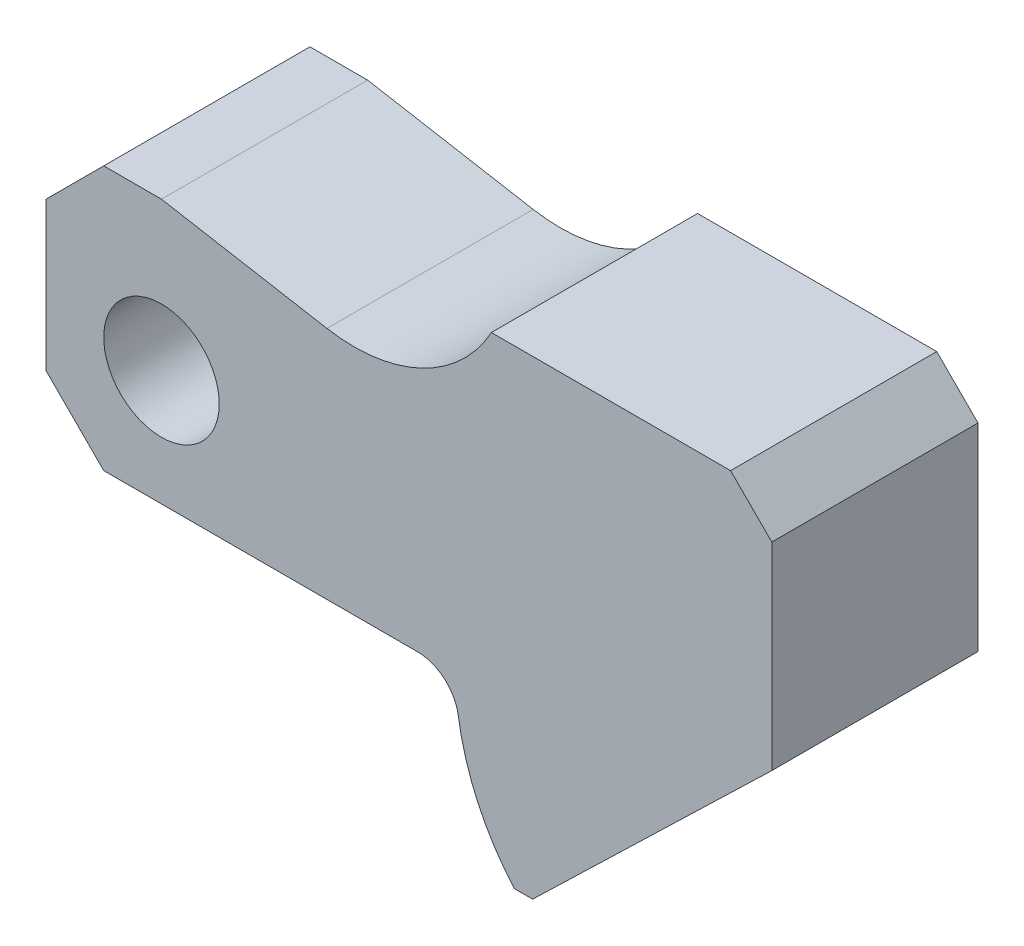
SolidWorks part; units mm, degrees
material "Brass"
ref_plane "Front Plane" through (0, 0, 0) normal (0, 0, 1) x (1, 0, 0)
ref_plane "Top Plane" through (0, 0, 0) normal (0, 1, 0) x (1, 0, 0)
ref_plane "Right Plane" through (0, 0, 0) normal (1, 0, 0) x (0, 0, -1)
sketch "Sketch1" plane through (0, 0, 0) normal (0, 0, 1) x (1, 0, 0)
  line L0 (0, 0) -> (-76.0965, 0)
  line L1 (-76.0965, 0) -> (-90.0965, 14)
  line L2 (-90.0965, 14) -> (-90.0965, 50)
  line L3 (-90.0965, 50) -> (-76.0965, 64)
  line L4 (-76.0965, 64) -> (-62.0965, 64)
  line L5 (-62.0965, 64) -> (-21.9721, 56.925)
  line L6 (17.9035, 76) -> (75.9035, 76)
  line L7 (75.9035, 76) -> (85.9035, 66)
  line L8 (85.9035, 66) -> (85.9035, 18)
  line L9 (85.9035, 18) -> (27.9035, -38)
  line L10 (27.9035, -38) -> (23.4429, -38)
  circle A0 centre (-62.0965, 28) radius 14
  arc A1 (17.9035, 76) -> (-21.9721, 56.925) centre (-15.3735, 94.3477) cw
  arc A2 (9.8913, -8.5294) -> (0, 0) centre (0, -10) ccw
  arc A3 (23.4429, -38) -> (9.8913, -8.5294) centre (67.2607, 0) cw
  point P17 (-23.4574, 57.1869)
  point P21 (6.1251, -17.9046)
  point P23 (0, 0)
  point P24 (23.4429, 94.3477)
  point P25 (17.9035, 77.3663)
  point P26 (0, 0)
  point P27 (0, 0)
  point P28 (-1.198, 0)
  dimension "D9" = 28
  dimension "D11" = 38
  dimension "D13" = 58
  dimension "D14" = 10
  dimension "D1" = 28
  dimension "D2" = 45
  dimension "D3" = 14
  dimension "D4" = 28
  dimension "D5" = 64
  dimension "D6" = 14
  dimension "D7" = 28
  dimension "D8" = 45
  dimension "D10" = 10
  dimension "D12" = 38
  dimension "D15" = 38
  dimension "D16" = 58
  dimension "D17" = 48
  dimension "D18" = 10
  dimension "D19" = 114
  dimension "D20" = 45
  dimension "D21" = 58
  dimension "D22" = 176
extrude "Boss-Extrude1" add sketch "Sketch1" along normal blind 50
